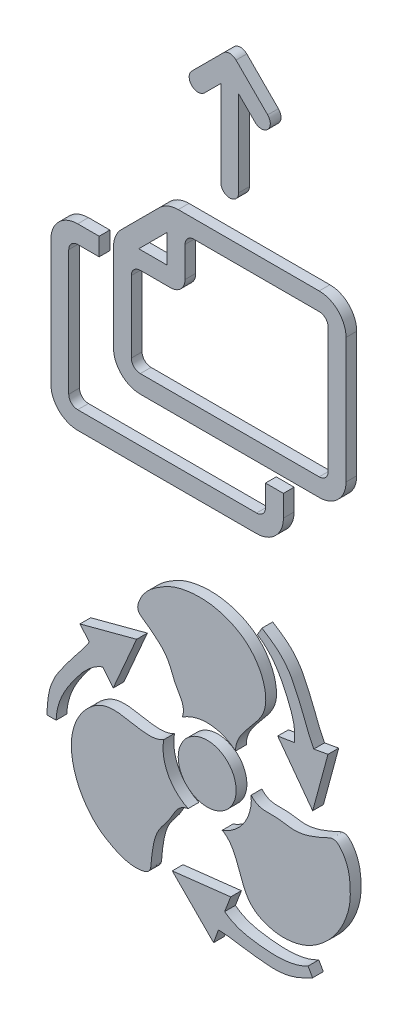
SolidWorks part; units mm, degrees
ref_plane "Plan de face" through (0, 0, 0) normal (0, 0, 1) x (1, 0, 0)
ref_plane "Plan de dessus" through (0, 0, 0) normal (0, 1, 0) x (1, 0, 0)
ref_plane "Plan de droite" through (0, 0, 0) normal (1, 0, 0) x (0, 0, -1)
sketch "Esquisse1" plane through (0, 0, 0) normal (0, 0, 1) x (1, 0, 0)
  line L0 (79.7187, -5.6862) -> (78.9221, -5.8311) construction
  line L1 (76.0254, -1.426) -> (75.7701, -1.8683) construction
  line L2 (77.8351, -6.0582) -> (76.9051, -6.2071) construction
  line L3 (76.9051, -6.2071) -> (78.8625, -8.8495) construction
  line L4 (78.8625, -8.8495) -> (79.7187, -5.6862) construction
  line L5 (65.8516, -6.3076) -> (66.3754, -6.925)
  line L6 (64.0089, -11.6362) -> (64.5195, -11.6362)
  line L7 (67.1156, -7.7529) -> (67.7095, -8.4839)
  line L8 (67.7095, -8.4839) -> (69.0193, -5.4674)
  line L9 (69.0193, -5.4674) -> (65.8516, -6.3076)
  line L10 (65.8516, -6.3076) -> (66.3754, -6.925)
  line L11 (64.0089, -11.6362) -> (64.5195, -11.6362)
  line L12 (67.1156, -7.7529) -> (67.7095, -8.4839)
  line L13 (67.7095, -8.4839) -> (69.0193, -5.4674)
  line L14 (69.0193, -5.4674) -> (65.8516, -6.3076)
  line L15 (73.3234, -18.0062) -> (73.5961, -17.2438)
  line L16 (78.8594, -16.9377) -> (78.6041, -16.4955)
  line L17 (73.943, -16.1889) -> (74.279, -15.309)
  line L18 (74.279, -15.309) -> (71.0119, -15.683)
  line L19 (71.0119, -15.683) -> (73.3234, -18.0062)
  line L20 (73.3234, -18.0062) -> (73.5961, -17.2438)
  line L21 (78.8594, -16.9377) -> (78.6041, -16.4955)
  line L22 (73.943, -16.1889) -> (74.279, -15.309)
  line L23 (74.279, -15.309) -> (71.0119, -15.683)
  line L24 (71.0119, -15.683) -> (73.3234, -18.0062)
  line L25 (79.7187, -5.6862) -> (78.9221, -5.8311)
  line L26 (76.0254, -1.426) -> (75.7701, -1.8683)
  line L27 (77.8351, -6.0582) -> (76.9051, -6.2071)
  line L28 (76.9051, -6.2071) -> (78.8625, -8.8495)
  line L29 (78.8625, -8.8495) -> (79.7187, -5.6862)
  line L30 (72.8112, 22.8787) -> (73.7254, 23.7929) construction
  line L31 (73.7254, 23.7929) -> (73.7254, 19) construction
  line L32 (74.7254, 19) -> (74.7254, 23.7929) construction
  line L33 (74.7254, 23.7929) -> (75.6396, 22.8787) construction
  line L34 (76.3467, 23.5858) -> (74.579, 25.3536) construction
  line L35 (73.8718, 25.3536) -> (72.1041, 23.5858) construction
  line L36 (69.2254, 6.5) -> (79.2254, 6.5) construction
  line L37 (80.7254, 8) -> (80.7254, 15) construction
  line L38 (79.2254, 16.5) -> (71.3467, 16.5) construction
  line L39 (70.2861, 16.0607) -> (68.1647, 13.9393) construction
  line L40 (67.7254, 12.8787) -> (67.7254, 8) construction
  line L41 (65.2254, 4.5) -> (65.2254, 11.5) construction
  line L42 (65.7254, 12) -> (66.9254, 12) construction
  line L43 (66.9254, 12) -> (66.9254, 13) construction
  line L44 (66.9254, 13) -> (65.7254, 13) construction
  line L45 (64.2254, 11.5) -> (64.2254, 4.5) construction
  line L46 (65.7254, 3) -> (75.7254, 3) construction
  line L47 (77.2254, 4.5) -> (77.2254, 5.7) construction
  line L48 (77.2254, 5.7) -> (76.2254, 5.7) construction
  line L49 (76.2254, 5.7) -> (76.2254, 4.5) construction
  line L50 (75.7254, 4) -> (65.7254, 4) construction
  line L51 (72.8112, 22.8787) -> (73.7254, 23.7929)
  line L52 (73.7254, 23.7929) -> (73.7254, 19)
  line L53 (74.7254, 19) -> (74.7254, 23.7929)
  line L54 (74.7254, 23.7929) -> (75.6396, 22.8787)
  line L55 (76.3467, 23.5858) -> (74.579, 25.3536)
  line L56 (73.8718, 25.3536) -> (72.1041, 23.5858)
  line L57 (69.2254, 6.5) -> (79.2254, 6.5)
  line L58 (80.7254, 8) -> (80.7254, 15)
  line L59 (79.2254, 16.5) -> (71.3467, 16.5)
  line L60 (70.2861, 16.0607) -> (68.1647, 13.9393)
  line L61 (67.7254, 12.8787) -> (67.7254, 8)
  line L62 (65.2254, 4.5) -> (65.2254, 11.5)
  line L63 (65.7254, 12) -> (66.9254, 12)
  line L64 (66.9254, 12) -> (66.9254, 13)
  line L65 (66.9254, 13) -> (65.7254, 13)
  line L66 (64.2254, 11.5) -> (64.2254, 4.5)
  line L67 (65.7254, 3) -> (75.7254, 3)
  line L68 (77.2254, 4.5) -> (77.2254, 5.7)
  line L69 (77.2254, 5.7) -> (76.2254, 5.7)
  line L70 (76.2254, 5.7) -> (76.2254, 4.5)
  line L71 (75.7254, 4) -> (65.7254, 4)
  line L75 (69.1396, 13.5) -> (70.7254, 13.5)
  line L76 (70.7254, 13.5) -> (70.7254, 15.0858)
  line L77 (70.7254, 15.0858) -> (69.1396, 13.5)
  line L78 (68.7254, 12) -> (68.7254, 8)
  line L79 (69.2254, 7.5) -> (79.2254, 7.5)
  line L80 (79.7254, 8) -> (79.7254, 15)
  line L81 (79.2254, 15.5) -> (72.2254, 15.5)
  line L82 (71.7254, 15) -> (71.7254, 13.3)
  line L83 (70.9254, 12.5) -> (69.2254, 12.5)
  line L84 (68.7254, 12) -> (68.7254, 8)
  line L85 (69.2254, 7.5) -> (79.2254, 7.5)
  line L86 (79.7254, 8) -> (79.7254, 15)
  line L87 (79.2254, 15.5) -> (72.2254, 15.5)
  line L88 (71.7254, 15) -> (71.7254, 13.3)
  line L89 (70.9254, 12.5) -> (69.2254, 12.5)
  line L90 (69.1396, 13.5) -> (70.7254, 13.5)
  line L91 (70.7254, 13.5) -> (70.7254, 15.0858)
  line L92 (70.7254, 15.0858) -> (69.1396, 13.5)
  arc A0 (73.806, -12.3188) -> (75.4239, -9.8094) centre (72.9646, -10) ccw construction
  arc A1 (70.5358, -9.5693) -> (71.9, -12.2251) centre (72.9646, -10) ccw
  arc A2 (70.5358, -9.5693) -> (71.9, -12.2251) centre (72.9646, -10) ccw
  arc A3 (74.552, -8.1119) -> (71.5698, -7.9655) centre (72.9646, -10) ccw
  arc A4 (74.552, -8.1119) -> (71.5698, -7.9655) centre (72.9646, -10) ccw
  circle A5 centre (72.9646, -10) radius 1.62 construction
  arc A6 (73.806, -12.3188) -> (75.4239, -9.8094) centre (72.9646, -10) ccw
  circle A7 centre (72.9646, -10) radius 1.62
  arc A8 (73.7254, 19) -> (74.7254, 19) centre (74.2254, 19) ccw construction
  arc A9 (75.6396, 22.8787) -> (76.3467, 23.5858) centre (75.9932, 23.2322) ccw construction
  arc A10 (74.579, 25.3536) -> (73.8718, 25.3536) centre (74.2254, 25) ccw construction
  arc A11 (72.1041, 23.5858) -> (72.8112, 22.8787) centre (72.4576, 23.2322) ccw construction
  arc A12 (67.7254, 8) -> (69.2254, 6.5) centre (69.2254, 8) ccw construction
  arc A13 (79.2254, 6.5) -> (80.7254, 8) centre (79.2254, 8) ccw construction
  arc A14 (80.7254, 15) -> (79.2254, 16.5) centre (79.2254, 15) ccw construction
  arc A15 (71.3467, 16.5) -> (70.2861, 16.0607) centre (71.3467, 15) ccw construction
  arc A16 (68.1647, 13.9393) -> (67.7254, 12.8787) centre (69.2254, 12.8787) ccw construction
  arc A17 (65.2254, 4.5) -> (65.7254, 4) centre (65.7254, 4.5) ccw construction
  arc A18 (65.7254, 12) -> (65.2254, 11.5) centre (65.7254, 11.5) ccw construction
  arc A19 (65.7254, 13) -> (64.2254, 11.5) centre (65.7254, 11.5) ccw construction
  arc A20 (64.2254, 4.5) -> (65.7254, 3) centre (65.7254, 4.5) ccw construction
  arc A21 (75.7254, 3) -> (77.2254, 4.5) centre (75.7254, 4.5) ccw construction
  arc A22 (75.7254, 4) -> (76.2254, 4.5) centre (75.7254, 4.5) ccw construction
  arc A23 (73.7254, 19) -> (74.7254, 19) centre (74.2254, 19) ccw
  arc A24 (75.6396, 22.8787) -> (76.3467, 23.5858) centre (75.9932, 23.2322) ccw
  arc A25 (74.579, 25.3536) -> (73.8718, 25.3536) centre (74.2254, 25) ccw
  arc A26 (72.1041, 23.5858) -> (72.8112, 22.8787) centre (72.4576, 23.2322) ccw
  arc A27 (67.7254, 8) -> (69.2254, 6.5) centre (69.2254, 8) ccw
  arc A28 (79.2254, 6.5) -> (80.7254, 8) centre (79.2254, 8) ccw
  arc A29 (80.7254, 15) -> (79.2254, 16.5) centre (79.2254, 15) ccw
  arc A30 (71.3467, 16.5) -> (70.2861, 16.0607) centre (71.3467, 15) ccw
  arc A31 (68.1647, 13.9393) -> (67.7254, 12.8787) centre (69.2254, 12.8787) ccw
  arc A32 (65.2254, 4.5) -> (65.7254, 4) centre (65.7254, 4.5) ccw
  arc A33 (65.7254, 12) -> (65.2254, 11.5) centre (65.7254, 11.5) ccw
  arc A34 (65.7254, 13) -> (64.2254, 11.5) centre (65.7254, 11.5) ccw
  arc A35 (64.2254, 4.5) -> (65.7254, 3) centre (65.7254, 4.5) ccw
  arc A36 (75.7254, 3) -> (77.2254, 4.5) centre (75.7254, 4.5) ccw
  arc A37 (75.7254, 4) -> (76.2254, 4.5) centre (75.7254, 4.5) ccw
  arc A44 (68.7254, 8) -> (69.2254, 7.5) centre (69.2254, 8) ccw
  arc A45 (79.2254, 7.5) -> (79.7254, 8) centre (79.2254, 8) ccw
  arc A46 (79.7254, 15) -> (79.2254, 15.5) centre (79.2254, 15) ccw
  arc A47 (72.2254, 15.5) -> (71.7254, 15) centre (72.2254, 15) ccw
  arc A48 (70.9254, 12.5) -> (71.7254, 13.3) centre (70.9254, 13.3) ccw
  arc A49 (69.2254, 12.5) -> (68.7254, 12) centre (69.2254, 12) ccw
  arc A50 (68.7254, 8) -> (69.2254, 7.5) centre (69.2254, 8) ccw
  arc A51 (79.2254, 7.5) -> (79.7254, 8) centre (79.2254, 8) ccw
  arc A52 (79.7254, 15) -> (79.2254, 15.5) centre (79.2254, 15) ccw
  arc A53 (72.2254, 15.5) -> (71.7254, 15) centre (72.2254, 15) ccw
  arc A54 (70.9254, 12.5) -> (71.7254, 13.3) centre (70.9254, 13.3) ccw
  arc A55 (69.2254, 12.5) -> (68.7254, 12) centre (69.2254, 12) ccw
  spline S0 degree 3 poles (1009.3928, 360.5348) (70.5566, -31.0519) (82.6129, -13.8487) (77.9456, -3.542) (77.5929, -2.7745) (70.2213, 5.9333) (30.9508, -24.518) (768.927, 719.5932) knots -5.678133 -5.678133 -5.678133 -5.678133 0.322858 0.451826 0.608228 0.790301 6.680438 6.680438 6.680438 6.680438 only from (78.9221, -5.8311) to (76.0254, -1.426) construction
  spline S1 degree 3 poles (-356.7738, 1944.136) (109.9533, -107.8604) (76.4689, -4.083) (66.3522, -10.0238) (65.6988, -10.8556) (65.3508, -11.9084) (65.3679, -12.9817) (65.672, -14.1036) (66.2485, -15.0455) (66.9262, -15.7476) (67.5915, -16.146) (68.2035, -16.4406) (68.8087, -16.5606) (69.288, -16.5387) (69.6603, -16.43) (69.8254, -16.1572) (69.8202, -15.7988) (69.9018, -15.2996) (69.9946, -14.6485) (70.283, -13.9494) (75.7591, -8.3828) (48.9837, 21.3139) (1600.9777, -1301.3324) knots -1.536984 -1.536984 -1.536984 -1.536984 0.177515 0.224652 0.289489 0.345336 0.400887 0.461026 0.531696 0.577426 0.617679 0.656656 0.687064 0.71613 0.735073 0.745884 0.765115 0.791853 0.828117 0.871557 0.91134 2.080973 2.080973 2.080973 2.080973 only from (70.5358, -9.5693) to (71.9, -12.2251)
  spline S2 degree 3 poles (70.5358, -9.5693) (69.5858, -10.1323) (67.9557, -9.0822) (66.3522, -10.0238) (65.6988, -10.8556) (65.3508, -11.9084) (65.3679, -12.9817) (65.672, -14.1036) (66.2485, -15.0455) (66.9262, -15.7476) (67.5915, -16.146) (68.2035, -16.4406) (68.8087, -16.5606) (69.288, -16.5387) (69.6603, -16.43) (69.8254, -16.1572) (69.8202, -15.7988) (69.9018, -15.2996) (69.9946, -14.6485) (70.283, -13.9494) (71.0343, -13.1857) (71.234, -12.3407) (71.9, -12.2251) knots 0 0 0 0 0.177515 0.224652 0.289489 0.345336 0.400887 0.461026 0.531696 0.577426 0.617679 0.656656 0.687064 0.71613 0.735073 0.745884 0.765115 0.791853 0.828117 0.871557 0.91134 1 1 1 1
  spline S3 degree 3 poles (1980.1651, -614.9036) (-30.2794, 6.8971) (76.3367, -15.9933) (76.2502, -4.2616) (75.8564, -3.2799) (75.1187, -2.4521) (74.1807, -1.9302) (73.057, -1.6326) (71.953, -1.6609) (71.0062, -1.8968) (70.3285, -2.2738) (69.7673, -2.6565) (69.3608, -3.1206) (69.1402, -3.5466) (69.0482, -3.9234) (69.2018, -4.2028) (69.5148, -4.3775) (69.9064, -4.6978) (70.4238, -5.1037) (70.8851, -5.703) (72.9678, -13.2287) (112.0736, -4.8889) (-1809.3687, -687.632) knots -1.536984 -1.536984 -1.536984 -1.536984 0.177515 0.224652 0.289489 0.345336 0.400887 0.461026 0.531696 0.577426 0.617679 0.656656 0.687064 0.71613 0.735073 0.745884 0.765115 0.791853 0.828117 0.871557 0.91134 2.080973 2.080973 2.080973 2.080973 only from (74.552, -8.1119) to (71.5698, -7.9655)
  spline S4 degree 3 poles (-1512.3726, 1220.6212) (103.7764, -3.1558) (73.0814, 2.523) (64.8812, -8.9153) (64.3929, -9.6044) (59.633, -22.8619) (131.5733, -48.6494) (-1873.501, 483.8733) knots -7.211488 -7.211488 -7.211488 -7.211488 0.322858 0.451826 0.608228 0.790301 8.141914 8.141914 8.141914 8.141914 only from (66.3754, -6.925) to (64.0089, -11.6362)
  spline S5 degree 3 poles (2033.7423, 332.9295) (108.841, -73.1956) (56.5707, -22.3338) (72.6702, 1.3397) (95.6367, 4.6405) (1260.8793, -1612.1076) knots -9.095259 -9.095259 -9.095259 -9.095259 0.353975 0.561821 8.617369 8.617369 8.617369 8.617369 only from (64.5195, -11.6362) to (67.1156, -7.7529)
  spline S6 degree 3 poles (66.3754, -6.925) (66.0716, -7.4234) (65.5191, -8.0256) (64.8812, -8.9153) (64.3929, -9.6044) (64.0536, -10.5495) (64.0183, -11.2595) (64.0089, -11.6362) knots 0 0 0 0 0.322858 0.451826 0.608228 0.790301 1 1 1 1
  spline S7 degree 3 poles (64.5195, -11.6362) (64.5336, -11.0571) (64.8377, -10.1777) (65.7466, -8.8412) (66.4282, -8.0251) (67.1156, -7.7529) knots 0 0 0 0 0.353975 0.561821 1 1 1 1
  spline S8 degree 3 poles (74.552, -8.1119) (74.5393, -7.0078) (76.2639, -6.1211) (76.2502, -4.2616) (75.8564, -3.2799) (75.1187, -2.4521) (74.1807, -1.9302) (73.057, -1.6326) (71.953, -1.6609) (71.0062, -1.8968) (70.3285, -2.2738) (69.7673, -2.6565) (69.3608, -3.1206) (69.1402, -3.5466) (69.0482, -3.9234) (69.2018, -4.2028) (69.5148, -4.3775) (69.9064, -4.6978) (70.4238, -5.1037) (70.8851, -5.703) (71.1708, -6.7355) (71.8028, -7.331) (71.5698, -7.9655) knots 0 0 0 0 0.177515 0.224652 0.289489 0.345336 0.400887 0.461026 0.531696 0.577426 0.617679 0.656656 0.687064 0.71613 0.735073 0.745884 0.765115 0.791853 0.828117 0.871557 0.91134 1 1 1 1
  spline S9 degree 3 poles (-293.5414, -931.173) (26.4068, -2.7637) (71.8717, 7.4833) (81.7603, -12.9889) (77.1997, -28.6518) (-913.8432, -134.6638) knots -7.115664 -7.115664 -7.115664 -7.115664 0.353975 0.561821 6.950462 6.950462 6.950462 6.950462 only from (75.7701, -1.8683) to (77.8351, -6.0582) construction
  spline S10 degree 3 poles (-200.1161, -1998.2528) (51.6314, 13.2618) (62.0609, -16.1603) (76.0668, -17.5427) (76.9078, -17.621) (90.7691, -15.1146) (77.1315, 60.0814) (618.4905, -1942.6253) knots -7.211488 -7.211488 -7.211488 -7.211488 0.322858 0.451826 0.608228 0.790301 8.141914 8.141914 8.141914 8.141914 only from (73.5961, -17.2438) to (78.8594, -16.9377)
  spline S11 degree 3 poles (-1204.41, 1516.6186) (109.7553, 52.6678) (91.8429, -18.0305) (63.2913, -15.9247) (48.9494, 2.3144) (866.4731, 1819.8182) knots -9.095259 -9.095259 -9.095259 -9.095259 0.353975 0.561821 8.617369 8.617369 8.617369 8.617369 only from (78.6041, -16.4955) to (73.943, -16.1889)
  spline S12 degree 3 poles (73.5961, -17.2438) (74.1796, -17.2578) (74.9774, -17.4352) (76.0668, -17.5427) (76.9078, -17.621) (77.8959, -17.4424) (78.5285, -17.118) (78.8594, -16.9377) knots 0 0 0 0 0.322858 0.451826 0.608228 0.790301 1 1 1 1
  spline S13 degree 3 poles (78.6041, -16.4955) (78.0955, -16.7729) (77.1819, -16.9492) (75.57, -16.8304) (74.5224, -16.6481) (73.943, -16.1889) knots 0 0 0 0 0.353975 0.561821 1 1 1 1
  spline S14 degree 3 poles (-670.2786, -680.3937) (114.3432, 42.8496) (67.9649, -10.9889) (76.2913, -15.7146) (77.3384, -15.8645) (78.4242, -15.6395) (79.3451, -15.0881) (80.1647, -14.2638) (80.6922, -13.2935) (80.9613, -12.3556) (80.9737, -11.5802) (80.9228, -10.9029) (80.7242, -10.3188) (80.4655, -9.9147) (80.1853, -9.6466) (79.8665, -9.64) (79.5587, -9.8237) (79.0855, -10.0026) (78.4752, -10.2478) (77.7256, -10.3477) (71.5943, -8.7585) (62.4684, -33.07) (246.6942, 975.4109) knots -1.201015 -1.201015 -1.201015 -1.201015 0.177515 0.224652 0.289489 0.345336 0.400887 0.461026 0.531696 0.577426 0.617679 0.656656 0.687064 0.71613 0.735073 0.745884 0.765115 0.791853 0.828117 0.871557 0.91134 1.844358 1.844358 1.844358 1.844358 only from (73.806, -12.3188) to (75.4239, -9.8094) construction
  spline S15 degree 3 poles (78.9221, -5.8311) (78.6424, -5.3189) (78.3972, -4.5392) (77.9456, -3.542) (77.5929, -2.7745) (76.9442, -2.0082) (76.3469, -1.6225) (76.0254, -1.426) knots 0 0 0 0 0.322858 0.451826 0.608228 0.790301 1 1 1 1
  spline S16 degree 3 poles (75.7701, -1.8683) (76.2646, -2.1701) (76.8741, -2.873) (77.5771, -4.3285) (77.943, -5.3268) (77.8351, -6.0582) knots 0 0 0 0 0.353975 0.561821 1 1 1 1
  spline S17 degree 3 poles (73.806, -12.3188) (74.7685, -12.8599) (74.6741, -14.7968) (76.2913, -15.7146) (77.3384, -15.8645) (78.4242, -15.6395) (79.3451, -15.0881) (80.1647, -14.2638) (80.6922, -13.2935) (80.9613, -12.3556) (80.9737, -11.5802) (80.9228, -10.9029) (80.7242, -10.3188) (80.4655, -9.9147) (80.1853, -9.6466) (79.8665, -9.64) (79.5587, -9.8237) (79.0855, -10.0026) (78.4752, -10.2478) (77.7256, -10.3477) (76.6886, -10.0789) (75.8569, -10.3283) (75.4239, -9.8094) knots 0 0 0 0 0.177515 0.224652 0.289489 0.345336 0.400887 0.461026 0.531696 0.577426 0.617679 0.656656 0.687064 0.71613 0.735073 0.745884 0.765115 0.791853 0.828117 0.871557 0.91134 1 1 1 1
  dimension "D1" = 0
  dimension "D2" = 0
  dimension "D3" = 0
  dimension "D4" = 0
  dimension "D5" = 0
  dimension "D6" = 0
extrude "Boss.-Extru.1" add sketch "Esquisse1" along normal up to surface (0.6 mm away)
